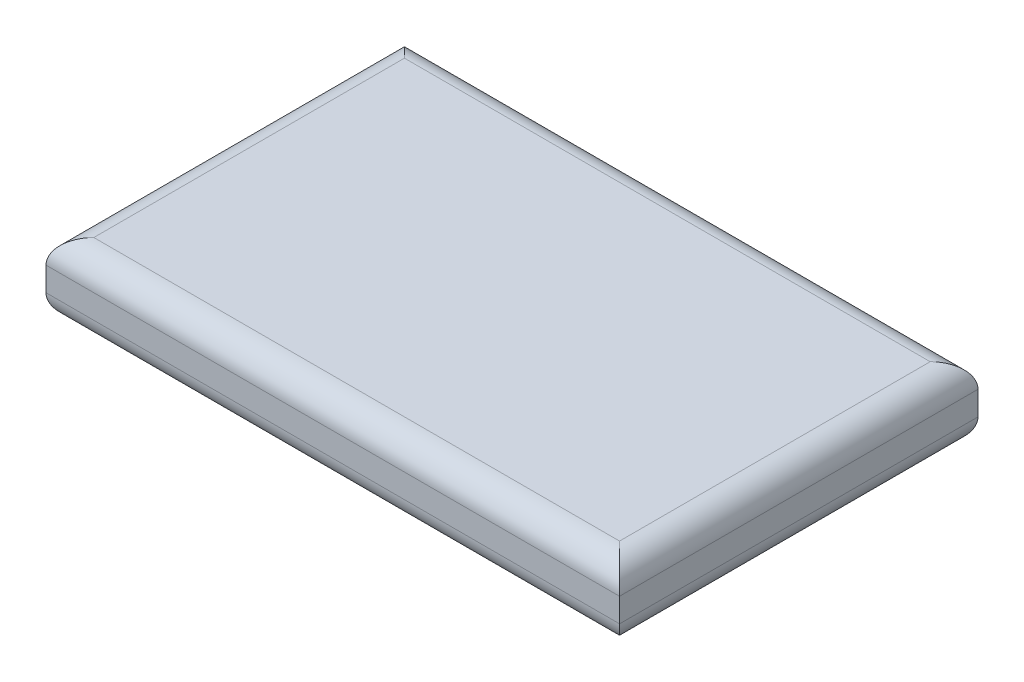
SolidWorks part; units mm, degrees
ref_plane "Front Plane" through (0, 0, 0) normal (0, 0, 1) x (1, 0, 0)
ref_plane "Top Plane" through (0, 0, 0) normal (0, 1, 0) x (1, 0, 0)
ref_plane "Right Plane" through (0, 0, 0) normal (1, 0, 0) x (0, 0, -1)
sketch "Sketch1" plane through (0, 0, 0) normal (0, 1, 0) x (1, 0, 0)
  line L1 (24.1258, -15.8709) -> (-23.8742, -15.8709)
  line L2 (24.1258, -15.8709) -> (24.1258, 14.1291)
  line L3 (24.1258, 14.1291) -> (-23.8742, 14.1291)
  line L4 (-23.8742, -15.8709) -> (-23.8742, 14.1291)
  dimension "D1" = 48
  dimension "D2" = 30
extrude "Boss-Extrude1" add sketch "Sketch1" along normal blind 6
fillet "Fillet1" radius 2 8 edges at (0.1258, 0, -14.1291) (-23.8742, 0, 0.8709) (0.1258, 0, 15.8709) (24.1258, 0, 0.8709) (0.1258, 6, 15.8709) (-23.8742, 6, 0.8709) (0.1258, 6, -14.1291) (24.1258, 6, 0.8709)
